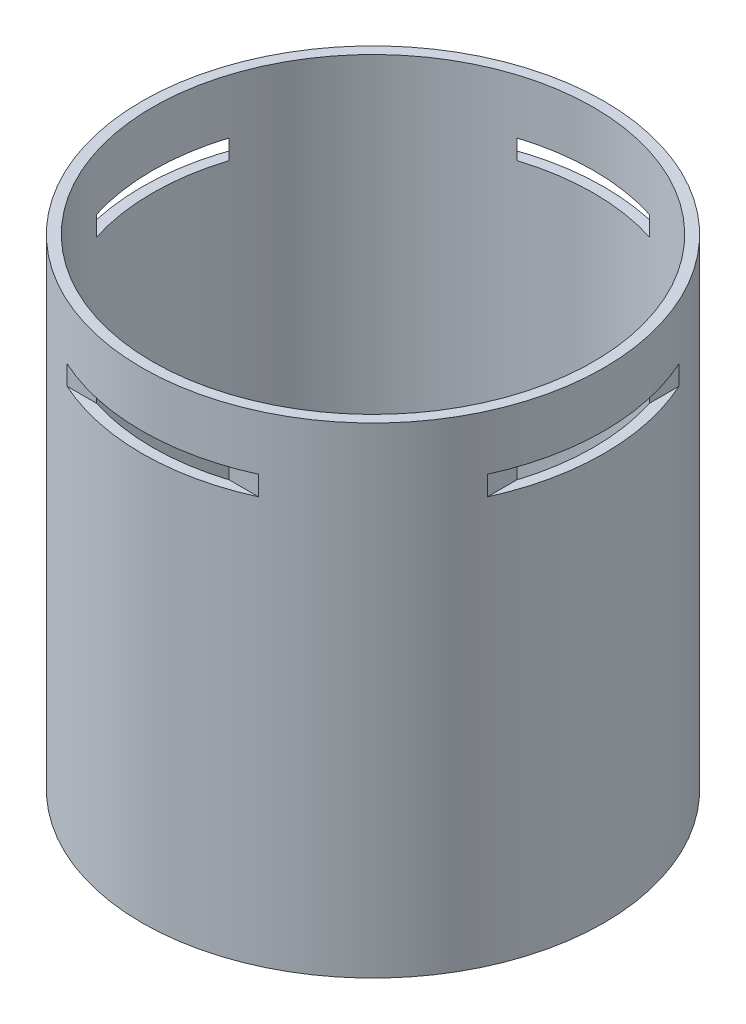
SolidWorks part; units mm, degrees
material "Chrome Stainless Steel"
ref_plane "Front Plane" through (0, 0, 0) normal (0, 0, 1) x (1, 0, 0)
ref_plane "Top Plane" through (0, 0, 0) normal (0, 1, 0) x (1, 0, 0)
ref_plane "Right Plane" through (0, 0, 0) normal (1, 0, 0) x (0, 0, -1)
sketch "Sketch1" plane through (0, 0, 0) normal (0, 1, 0) x (1, 0, 0)
  circle A0 centre (0, 0) radius 29.55
  dimension "D1" = 59.1
extrude "Boss-Extrude1" add sketch "Sketch1" along normal blind 61.5
sketch "Sketch2" plane through (0, 61.5, 0) normal (0, 1, 0) x (1, 0, 0)
  circle A0 centre (0, 0) radius 28.2
  dimension "D1" = 56.4
extrude "Cut-Extrude1" cut sketch "Sketch2" against normal blind 61.5
ref_plane "Plane1" through (0, 54.5, 0) normal (0, 1, 0) x (1, 0, 0)
sketch "Sketch3" plane through (0, 54.5, 0) normal (0, 1, 0) x (1, 0, 0)
  line L0 (0, 0) -> (0, 29.55) construction
  line L1 (-12.25, 26.8913) -> (12.25, 26.8913)
  line L2 (26.8913, 12.25) -> (26.8913, -12.25)
  line L3 (12.25, -26.8913) -> (-12.25, -26.8913)
  line L4 (-26.8913, -12.25) -> (-26.8913, 12.25)
  circle A0 centre (0, 0) radius 29.55 construction
  arc A1 (-12.25, 26.8913) -> (12.25, 26.8913) centre (0, 0) cw
  arc A2 (26.8913, 12.25) -> (26.8913, -12.25) centre (0, 0) cw
  arc A3 (12.25, -26.8913) -> (-12.25, -26.8913) centre (0, 0) cw
  arc A4 (-26.8913, -12.25) -> (-26.8913, 12.25) centre (0, 0) cw
  point P20 (0, 0)
  dimension "D1" = 24.5
  dimension "D2" = 4
extrude "Cut-Extrude2" cut sketch "Sketch3" against normal blind 2.5
